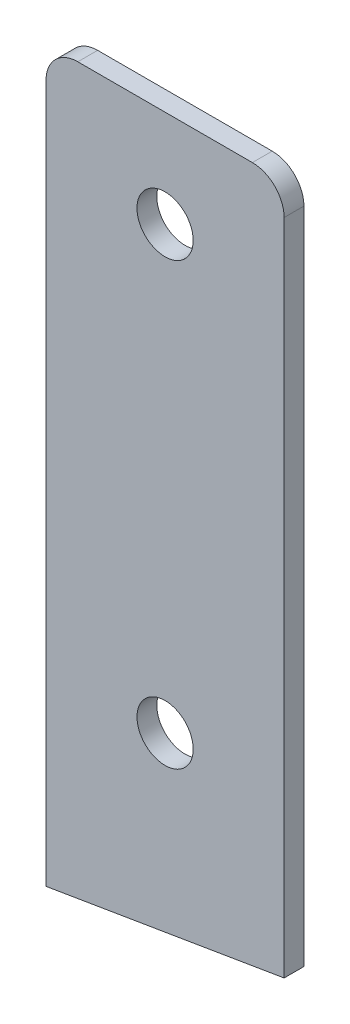
SolidWorks part; units mm, degrees
material "ASTM A36 Steel"
ref_plane "X-Y Datum" through (0, 0, 0) normal (0, 0, 1) x (1, 0, 0)
ref_plane "X-Z Datum" through (0, 0, 0) normal (0, 1, 0) x (1, 0, 0)
ref_plane "Y-Z Datum" through (0, 0, 0) normal (1, 0, 0) x (0, 0, -1)
sketch "Sketch1" plane through (0, 0, 0) normal (0, 0, 1) x (1, 0, 0)
  line L0 (0, 17.6276) -> (0, -17.6276)
  line L1 (-9.525, 25.4) -> (9.525, 25.4)
  line L2 (-9.525, 25.4) -> (-9.525, -25.4)
  line L3 (-9.525, -25.4) -> (9.525, -25.4)
  line L4 (9.525, 25.4) -> (9.525, -25.4)
  line L5 (-9.525, 25.4) -> (9.525, -25.4) construction
  line L6 (-9.525, -25.4) -> (9.525, 25.4) construction
  point P0 (0, 0)
  point P9 (0, 0)
  point P10 (0, 17.6276)
  point P11 (0, -17.6276)
  dimension "D1" = 35.2552
  dimension "D2" = 19.05
  dimension "D3" = 50.8
extrude "Boss-Extrude1" add sketch "Sketch1" along normal blind 1.5875
hole_wizard "M4 Clearance Hole1" positions "Sketch2" profile "Sketch3" hole size "M4" standard "ANSI Metric" end condition through all
sketch "Sketch2" plane through (0, 0, 1.5875) normal (0, 0, 1) x (1, 0, 0)
  point P0 (0, 17.6276)
  point P3 (0, -17.6276)
sketch "Sketch3" plane through (0, 17.6276, 1.5875) normal (1, 0, 0) x (0, -1, 0)
  line L0 (0, 0) -> (0, 1.5875)
  line L1 (0, 1.5875) -> (2.25, 1.5875)
  line L2 (2.25, 1.5875) -> (2.25, 0)
  line L5 (2.25, 0) -> (0, 0)
  line L11 (0, -6.35) -> (0, 107.95) construction
  dimension "Thru Hole Dia." = 4.5
  dimension "Thru Hole Depth" = 1.5875
sketch "Sketch4" plane through (0, 0, 1.5875) normal (0, 0, 1) x (1, 0, 0)
  line L0 (9.525, 25.4) -> (9.525, -25.4) construction
  line L1 (-9.525, -25.4) -> (9.525, -25.4)
  line L2 (-9.525, -25.4) -> (-9.525, -33.02)
  line L3 (-9.525, -33.02) -> (9.525, -33.02)
  line L4 (9.525, -25.4) -> (9.525, -33.02)
  dimension "D1" = 7.62
extrude "Boss-Extrude2" add sketch "Sketch4" against normal blind 1.5875
fillet "Fillet1" radius 2.54 2 edges at (-9.525, 25.4, 0.7937) (9.525, 25.4, 0.7937)
sketch "Sketch5" plane through (0, 0, 1.5875) normal (0, 0, 1) x (1, 0, 0)
  line L0 (-9.525, -33.02) -> (9.525, -29.845)
  line L1 (-9.525, 22.86) -> (-9.525, -33.02) construction
  line L2 (-9.525, -33.02) -> (9.525, -33.02) construction
  line L3 (9.525, 22.86) -> (9.525, -33.02) construction
  line M7 (-9.525, -33.02) -> (9.525, -33.02)
  line M8 (9.525, -33.02) -> (9.525, 22.86)
  dimension "D1" = 3.175
extrude "Cut-Extrude1" cut sketch "Sketch5" against normal through all and the other way through all contours L0 M7 M8
